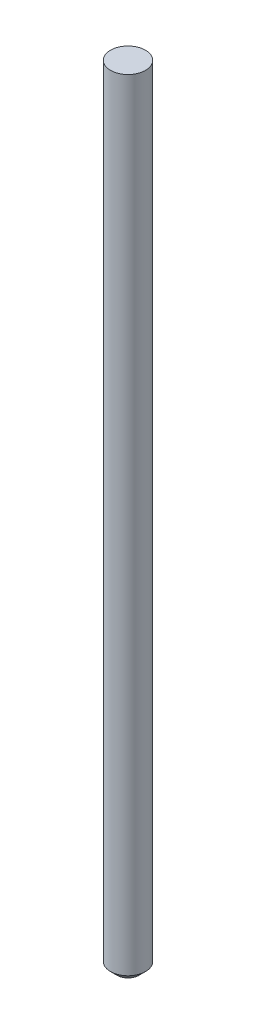
SolidWorks part; units mm, degrees
ref_plane "Front Plane" through (0, 0, 0) normal (0, 0, 1) x (1, 0, 0)
ref_plane "Top Plane" through (0, 0, 0) normal (0, 1, 0) x (1, 0, 0)
ref_plane "Right Plane" through (0, 0, 0) normal (1, 0, 0) x (0, 0, -1)
sketch "Sketch1" plane through (0, 0, 0) normal (0, 1, 0) x (1, 0, 0)
  circle A0 centre (0, 0) radius 4
  dimension "D1" = 8
extrude "Boss-Extrude1" add sketch "Sketch1" along normal blind 180
chamfer "Chamfer1" distance 1.5 angle 45 1 edges at (0, 0, 4)
